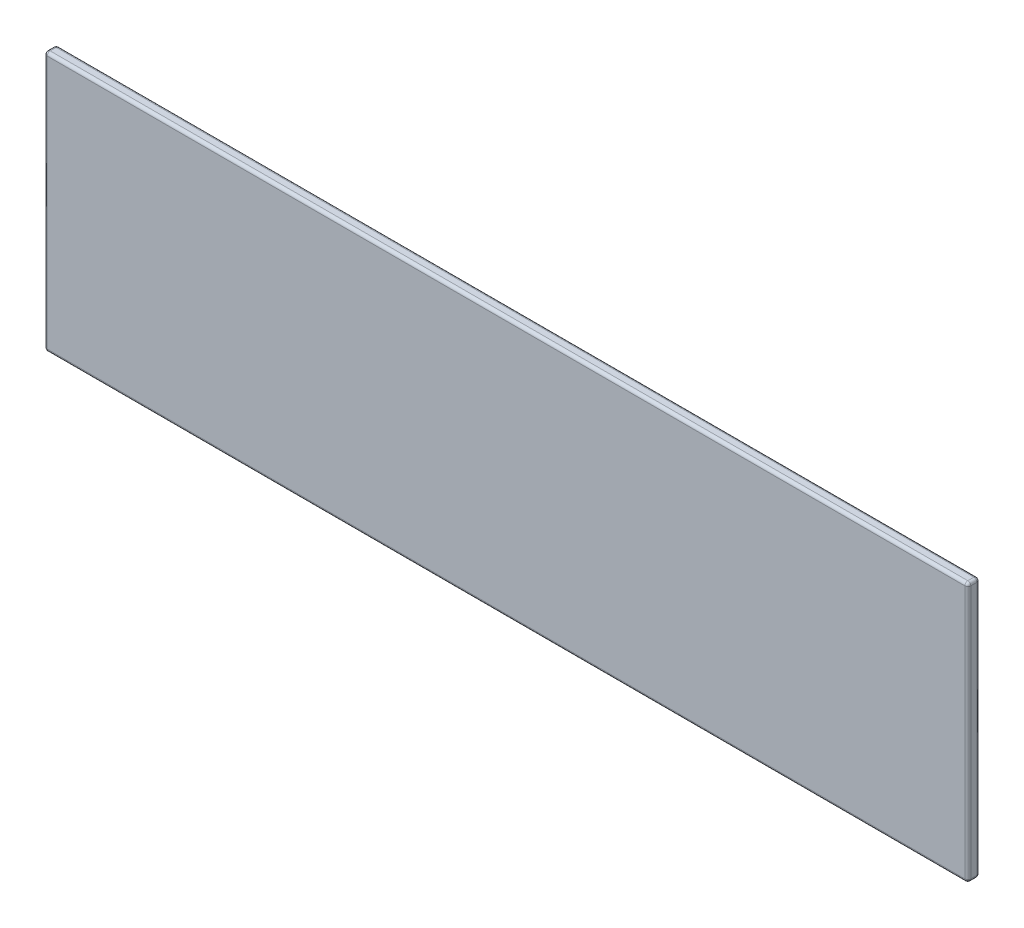
SolidWorks part; units mm, degrees
ref_plane "Front Plane" through (0, 0, 0) normal (0, 0, 1) x (1, 0, 0)
ref_plane "Top Plane" through (0, 0, 0) normal (0, 1, 0) x (1, 0, 0)
ref_plane "Right Plane" through (0, 0, 0) normal (1, 0, 0) x (0, 0, -1)
sketch "Sketch1" plane through (0, 0, 0) normal (0, 0, 1) x (1, 0, 0)
  line L1 (-77.35, -21.75) -> (77.35, -21.75)
  line L2 (-77.35, -21.75) -> (-77.35, 21.75)
  line L3 (-77.35, 21.75) -> (77.35, 21.75)
  line L4 (77.35, -21.75) -> (77.35, 21.75)
  line L5 (-77.35, -21.75) -> (77.35, 21.75) construction
  line L6 (-77.35, 21.75) -> (77.35, -21.75) construction
  point P0 (0, 0)
  dimension "D1" = 154.7
  dimension "D2" = 43.5
extrude "Boss-Extrude1" add sketch "Sketch1" along normal blind 2
fillet "Fillet1" radius 0.5 12 edges at (0, -21.75, 2) (0, -21.75, 0) (-77.35, 0, 2) (-77.35, -21.75, 1) (-77.35, 0, 0) (0, 21.75, 2) (-77.35, 21.75, 1) (0, 21.75, 0) (77.35, -21.75, 1) (77.35, 0, 2) (77.35, 21.75, 1) (77.35, 0, 0)
